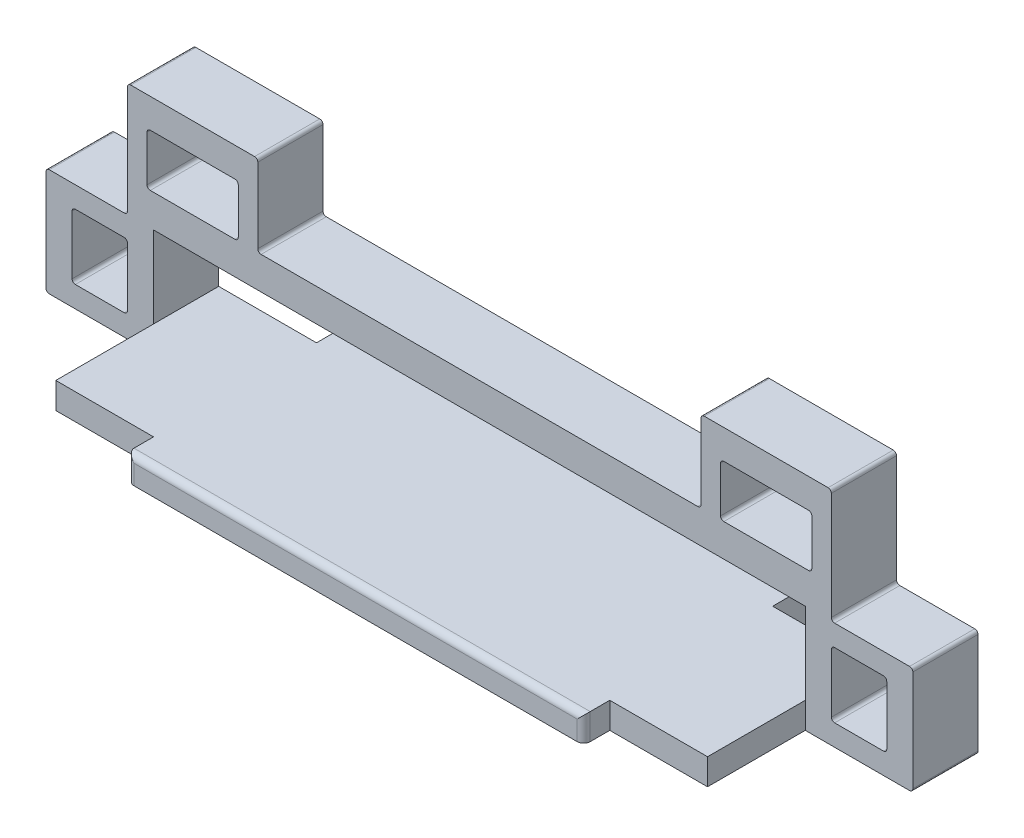
SolidWorks part; units mm, degrees
ref_plane "정면" through (0, 0, 0) normal (0, 0, 1) x (1, 0, 0)
ref_plane "윗면" through (0, 0, 0) normal (0, 1, 0) x (1, 0, 0)
ref_plane "우측면" through (0, 0, 0) normal (1, 0, 0) x (0, 0, -1)
sketch "스케치2" plane through (0, 0, 0) normal (0, 1, 0) x (1, 0, 0)
  line L1 (-117.4603, 98.9683) -> (82.5397, 98.9683)
  line L2 (-117.4603, 98.9683) -> (-117.4603, 48.9683)
  line L3 (-117.4603, 48.9683) -> (82.5397, 48.9683)
  line L4 (82.5397, 98.9683) -> (82.5397, 48.9683)
  dimension "D1" = 200
  dimension "D2" = 50
extrude "보스-돌출1" add sketch "스케치2" along normal blind 8
ref_plane "평면1" through (0, 33, 0) normal (0, -1, 0) x (-1, 0, 0)
sketch "스케치5" plane through (0, 33, 0) normal (0, -1, 0) x (1, 0, 0)
  line L1 (-125.4603, -78.9683) -> (-117.4603, -78.9683)
  line L2 (-125.4603, -78.9683) -> (-125.4603, -98.9683)
  line L3 (-125.4603, -98.9683) -> (-117.4603, -98.9683)
  line L4 (-117.4603, -78.9683) -> (-117.4603, -98.9683)
  line L5 (-117.4603, -98.9683) -> (-117.4603, -48.9683) construction
  line L6 (82.5397, -98.9683) -> (-117.4603, -98.9683) construction
  line L7 (90.5397, -78.9683) -> (82.5397, -78.9683)
  line L8 (90.5397, -78.9683) -> (90.5397, -98.9683)
  line L9 (90.5397, -98.9683) -> (82.5397, -98.9683)
  line L10 (82.5397, -78.9683) -> (82.5397, -98.9683)
extrude "보스-돌출6" add sketch "스케치5" along normal up to vertex (33 mm away) up to point (-117.4603, 0, -98.9682)
sketch "스케치7" plane through (0, 33, 0) normal (0, 1, 0) x (1, 0, 0)
  line L1 (-125.4603, 78.9683) -> (90.5397, 78.9683)
  line L2 (-125.4603, 78.9683) -> (-125.4603, 98.9683)
  line L3 (-125.4603, 98.9683) -> (90.5397, 98.9683)
  line L4 (90.5397, 78.9683) -> (90.5397, 98.9683)
extrude "보스-돌출7" add sketch "스케치7" along normal blind 10
sketch "스케치8" plane through (0, 8, 0) normal (0, 1, 0) x (1, 0, 0)
  line L0 (-117.4603, 48.9683) -> (82.5397, 48.9683) construction
  line L1 (-87.4603, 48.9683) -> (52.5397, 48.9683)
  line L2 (-87.4603, 48.9683) -> (-87.4603, 40.9683)
  line L3 (-87.4603, 40.9683) -> (52.5397, 40.9683)
  line L4 (52.5397, 48.9683) -> (52.5397, 40.9683)
  line L5 (82.5397, 48.9683) -> (82.5397, 78.9683) construction
  dimension "D1" = 8
  dimension "D2" = 140
  dimension "D3" = 30
extrude "보스-돌출8" add sketch "스케치8" against normal up to vertex (8 mm away)
sketch "스케치9" plane through (0, 8, 0) normal (0, 1, 0) x (1, 0, 0)
  line L1 (90.5397, 98.9683) -> (-125.4603, 98.9683) construction
  line L7 (52.5397, 98.9683) -> (52.5397, 108.9683)
  line L10 (52.5397, 40.9683) -> (52.5397, 48.9683) construction
  line L15 (-87.4603, 98.9683) -> (52.5397, 98.9683)
  line L16 (-87.4603, 98.9683) -> (-87.4603, 108.9683)
  line L17 (-87.4603, 108.9683) -> (52.5397, 108.9683)
  dimension "D3" = 10
  dimension "D4" = 10
extrude "보스-돌출9" add sketch "스케치9" against normal blind 24
sketch "스케치10" plane through (0, 0, -98.9683) normal (0, 0, 1) x (1, 0, 0)
  line L0 (-87.4603, -16) -> (-87.4603, 0) construction
  line L1 (-67.4603, -16) -> (-87.4603, -16)
  line L2 (-67.4603, -16) -> (-67.4603, -8)
  line L3 (-67.4603, -8) -> (-87.4603, -8)
  line L4 (-87.4603, -16) -> (-87.4603, -8)
  line L6 (32.5397, -16) -> (52.5397, -16)
  line L7 (32.5397, -16) -> (32.5397, -8)
  line L8 (32.5397, -8) -> (52.5397, -8)
  line L9 (52.5397, -16) -> (52.5397, -8)
  line L10 (-87.4603, -16) -> (52.5397, -16) construction
  dimension "D1" = 8
  dimension "D2" = 8
extrude "보스-돌출10" add sketch "스케치10" along normal blind 30
fillet "필렛1" radius 2 3 edges at (52.5397, 4, -40.9683) (-87.4603, 4, -40.9683) (-17.4603, 8, -40.9683)
sketch "스케치11" plane through (0, 43, 0) normal (0, 1, 0) x (1, 0, 0)
  line L0 (90.5397, 98.9683) -> (-125.4603, 98.9683) construction
  line L1 (-125.4603, 98.9683) -> (-85.4603, 98.9683)
  line L2 (-125.4603, 98.9683) -> (-125.4603, 78.9683)
  line L3 (-125.4603, 78.9683) -> (-85.4603, 78.9683)
  line L4 (-85.4603, 98.9683) -> (-85.4603, 78.9683)
  line L5 (-125.4603, 78.9683) -> (90.5397, 78.9683) construction
  line L7 (50.5397, 98.9683) -> (90.5397, 98.9683)
  line L8 (50.5397, 98.9683) -> (50.5397, 78.9683)
  line L9 (50.5397, 78.9683) -> (90.5397, 78.9683)
  line L10 (90.5397, 98.9683) -> (90.5397, 78.9683)
  line L11 (90.5397, 78.9683) -> (90.5397, 98.9683) construction
  dimension "D1" = 40
  dimension "D2" = 40
extrude "보스-돌출11" add sketch "스케치11" along normal blind 25
sketch "스케치12" plane through (0, 0, -78.9683) normal (0, 0, 1) x (1, 0, 0)
  line L1 (-91.4603, 43) -> (-119.4603, 43)
  line L2 (-91.4603, 43) -> (-91.4603, 59)
  line L3 (-91.4603, 59) -> (-119.4603, 59)
  line L4 (-119.4603, 43) -> (-119.4603, 59)
  line L5 (-125.4603, 0) -> (-125.4603, 68) construction
  line L6 (-85.4603, 43) -> (50.5397, 43) construction
  line L7 (84.5397, 43) -> (56.5397, 43)
  line L8 (84.5397, 43) -> (84.5397, 59)
  line L9 (84.5397, 59) -> (56.5397, 59)
  line L10 (56.5397, 43) -> (56.5397, 59)
  line L11 (50.5397, 68) -> (50.5397, 43) construction
  dimension "D1" = 28
  dimension "D2" = 16
  dimension "D3" = 6
  dimension "D4" = 28
  dimension "D5" = 16
  dimension "D6" = 6
extrude "컷-돌출1" cut sketch "스케치12" against normal through all both and the other way through all
sketch "스케치13" plane through (90.5397, 0, 0) normal (1, 0, 0) x (0, 0, -1)
  line L0 (98.9683, 0) -> (98.9683, 68) construction
  line L1 (78.9683, 33) -> (98.9683, 33)
  line L2 (78.9683, 33) -> (78.9683, 0)
  line L3 (78.9683, 0) -> (98.9683, 0)
  line L4 (98.9683, 33) -> (98.9683, 0)
extrude "보스-돌출12" add sketch "스케치13" along normal blind 25
sketch "스케치14" plane through (-125.4603, 0, 0) normal (-1, 0, 0) x (0, 0, 1)
  line L0 (-31.9, 33) -> (31.9, 33) construction
  line L1 (-98.9683, 0) -> (-78.9683, 0)
  line L2 (-98.9683, 0) -> (-98.9683, 33)
  line L3 (-98.9683, 33) -> (-78.9683, 33)
  line L4 (-78.9683, 0) -> (-78.9683, 33)
extrude "보스-돌출13" add sketch "스케치14" along normal blind 25
sketch "스케치15" plane through (0, 0, -78.9683) normal (0, 0, 1) x (1, 0, 0)
  line L0 (-125.4603, 33) -> (-125.4603, 68) construction
  line L1 (-142.4603, 26.5) -> (-125.4603, 26.5)
  line L2 (-142.4603, 26.5) -> (-142.4603, 6.5)
  line L3 (-142.4603, 6.5) -> (-125.4603, 6.5)
  line L4 (-125.4603, 26.5) -> (-125.4603, 6.5)
  line L6 (-31.9, 33) -> (31.9, 33) construction
  line L7 (-117.4603, 0) -> (-150.4603, 0) construction
  line L8 (90.5397, 26.5) -> (107.5397, 26.5)
  line L9 (90.5397, 26.5) -> (90.5397, 6.5)
  line L10 (90.5397, 6.5) -> (107.5397, 6.5)
  line L11 (107.5397, 26.5) -> (107.5397, 6.5)
  line L12 (90.5397, 33) -> (90.5397, 68) construction
  dimension "D1" = 17
  dimension "D2" = 20
  dimension "D3" = 6.5
  dimension "D4" = 6.5
  dimension "D5" = 17
  dimension "D6" = 20
  dimension "D7" = 6.5
  dimension "D8" = 0
extrude "컷-돌출2" cut sketch "스케치15" against normal through all both and the other way through all
fillet "필렛2" radius 1 28 edges at (115.5397, 0, -88.9683) (115.5397, 33, -88.9683) (107.5397, 6.5, -88.9683) (90.5397, 6.5, -88.9683) (107.5397, 26.5, -88.9683) (90.5397, 33, -88.9683) (84.5397, 43, -88.9683) (90.5397, 68, -88.9683) (90.5397, 26.5, -88.9683) (50.5397, 43, -88.9683) (50.5397, 68, -88.9683) (-85.4603, 43, -88.9683) (-91.4603, 43, -88.9683) (-119.4603, 43, -88.9683) (-91.4603, 59, -88.9683) (-119.4603, 59, -88.9683) (-85.4603, 68, -88.9683) (-125.4603, 68, -88.9683) (-125.4603, 33, -88.9683) (-150.4603, 0, -88.9683) (-150.4603, 33, -88.9683) (-125.4603, 6.5, -88.9683) (-142.4603, 26.5, -88.9683) (-125.4603, 26.5, -88.9683) (-142.4603, 6.5, -88.9683) (56.5397, 43, -88.9683) (84.5397, 59, -88.9683) (56.5397, 59, -88.9683)
